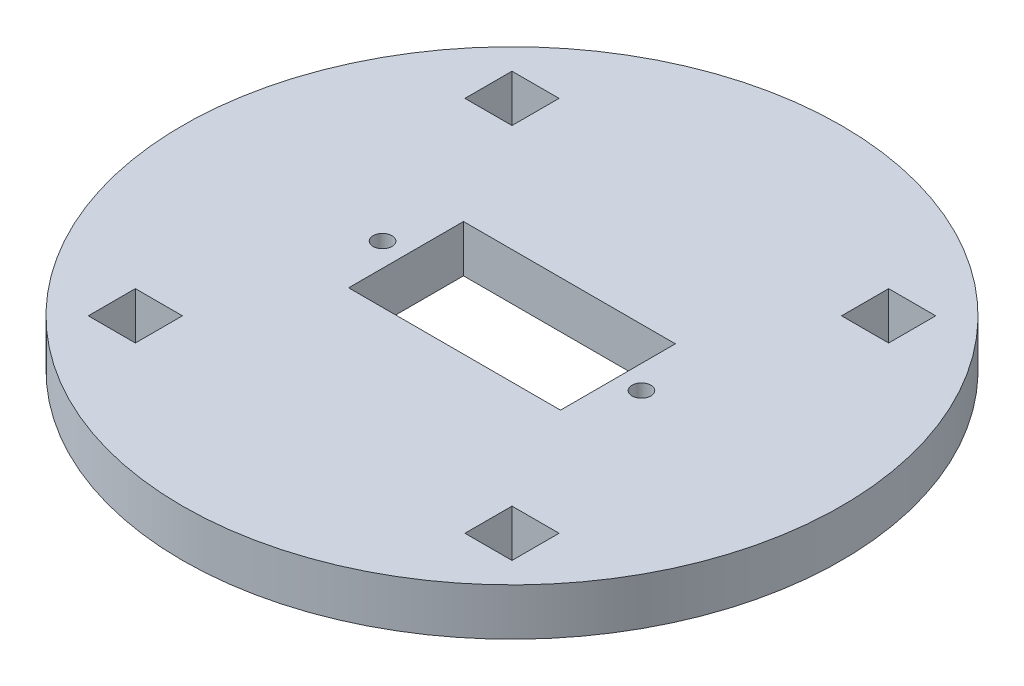
SolidWorks part; units mm, degrees
ref_plane "Front Plane" through (0, 0, 0) normal (0, 0, 1) x (1, 0, 0)
ref_plane "Top Plane" through (0, 0, 0) normal (0, 1, 0) x (1, 0, 0)
ref_plane "Right Plane" through (0, 0, 0) normal (1, 0, 0) x (0, 0, -1)
sketch "Sketch1" plane through (0, 0, 0) normal (0, 1, 0) x (1, 0, 0)
  line L1 (-11.25, -6.1) -> (11.25, -6.1)
  line L2 (-11.25, -6.1) -> (-11.25, 6.1)
  line L3 (-11.25, 6.1) -> (11.25, 6.1)
  line L4 (11.25, -6.1) -> (11.25, 6.1)
  line L5 (-11.25, -6.1) -> (11.25, 6.1) construction
  line L6 (-11.25, 6.1) -> (11.25, -6.1) construction
  line L7 (-22.5, -17.5) -> (-17.5, -17.5)
  line L8 (-22.5, -17.5) -> (-22.5, -22.5)
  line L9 (-22.5, -22.5) -> (-17.5, -22.5)
  line L10 (-17.5, -17.5) -> (-17.5, -22.5)
  line L11 (-22.5, -17.5) -> (-17.5, -22.5) construction
  line L12 (-22.5, -22.5) -> (-17.5, -17.5) construction
  line L24 (-17.5, 22.5) -> (-22.5, 22.5)
  line L29 (-20, -20) -> (20, 20) construction
  line L30 (-20, 20) -> (20, -20) construction
  line L31 (-17.5, 22.5) -> (-17.5, 17.5)
  line L32 (-17.5, 17.5) -> (-22.5, 17.5)
  line L33 (-22.5, 22.5) -> (-22.5, 17.5)
  line L34 (22.5, 17.5) -> (22.5, 22.5)
  line L35 (22.5, 17.5) -> (17.5, 17.5)
  line L36 (17.5, 17.5) -> (17.5, 22.5)
  line L37 (22.5, 22.5) -> (17.5, 22.5)
  line L38 (17.5, -22.5) -> (22.5, -22.5)
  line L39 (17.5, -22.5) -> (17.5, -17.5)
  line L40 (17.5, -17.5) -> (22.5, -17.5)
  line L41 (22.5, -22.5) -> (22.5, -17.5)
  circle A0 centre (0, 0) radius 35
  circle A1 centre (13.75, 0) radius 1
  circle A2 centre (-13.75, 0) radius 1
  point P10 (0, 0)
  point P12 (-20, -20)
  point P32 (0, 0)
  point P37 (0, 0)
  dimension "D1" = 70
  dimension "D5" = 2
  dimension "D6" = 2
  dimension "D2" = 12.2
  dimension "D3" = 22.5
  dimension "D4" = 27.5
  dimension "D7" = 5
  dimension "D8" = 5
  dimension "D9" = 40
  dimension "D10" = 4
extrude "Boss-Extrude1" add sketch "Sketch1" along normal blind 5
